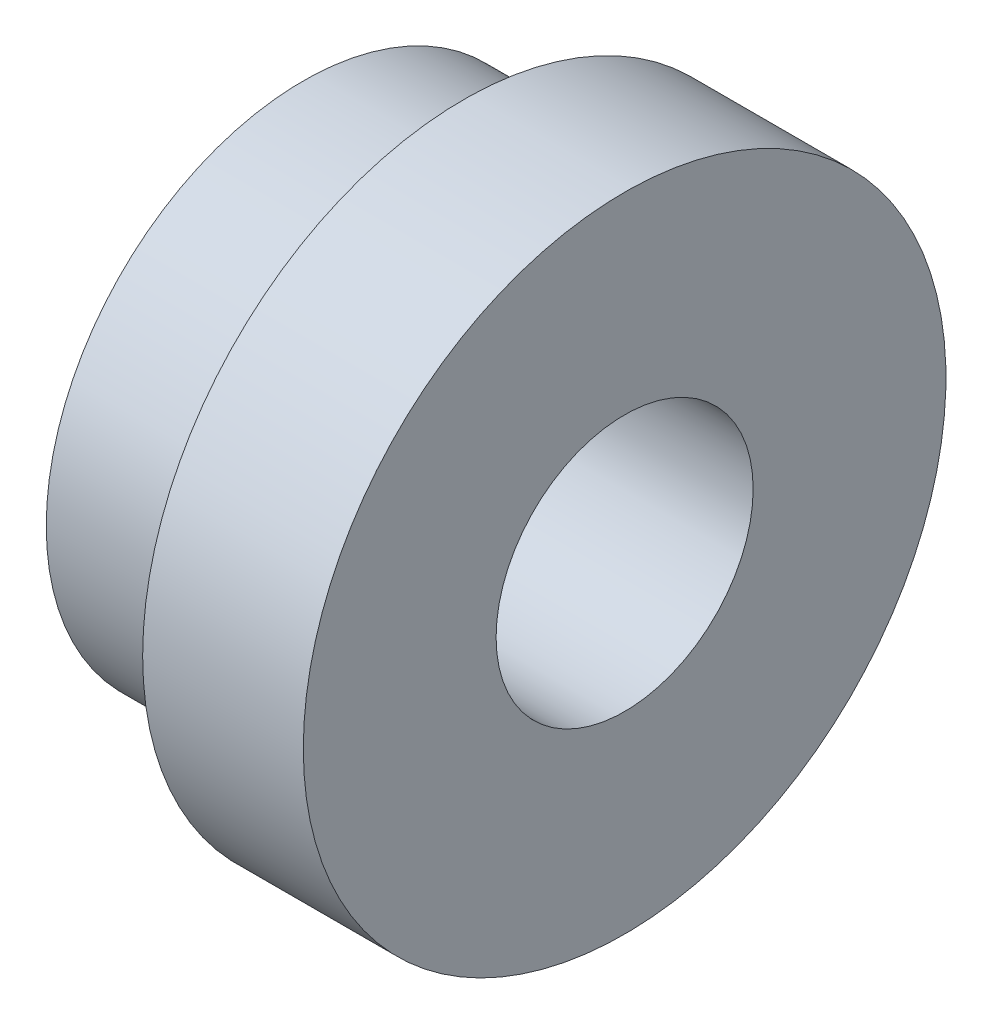
SolidWorks part; units mm, degrees
material "ABS"
ref_plane "Спереди" through (0, 0, 0) normal (0, 0, 1) x (1, 0, 0)
ref_plane "Сверху" through (0, 0, 0) normal (0, 1, 0) x (1, 0, 0)
ref_plane "Справа" through (0, 0, 0) normal (1, 0, 0) x (0, 0, -1)
sketch "Эскиз1" plane through (0, 0, 0) normal (0, 0, 1) x (1, 0, 0)
  line L0 (0, 0.8) -> (0, 1.6)
  line L1 (0, 1.6) -> (1, 1.6)
  line L2 (1, 1.6) -> (1, 2)
  line L3 (1, 2) -> (2, 2)
  line L4 (2, 2) -> (2, 0.8)
  line L5 (2, 0.8) -> (0, 0.8)
  line L6 (0, 0) -> (11968.7992, 0) construction
  dimension "D1" = 3.2
  dimension "D2" = 4
  dimension "D3" = 1
  dimension "D4" = 1
  dimension "D5" = 1.6
revolve "Повернуть1" add sketch "Эскиз1" angle 360 about L6
